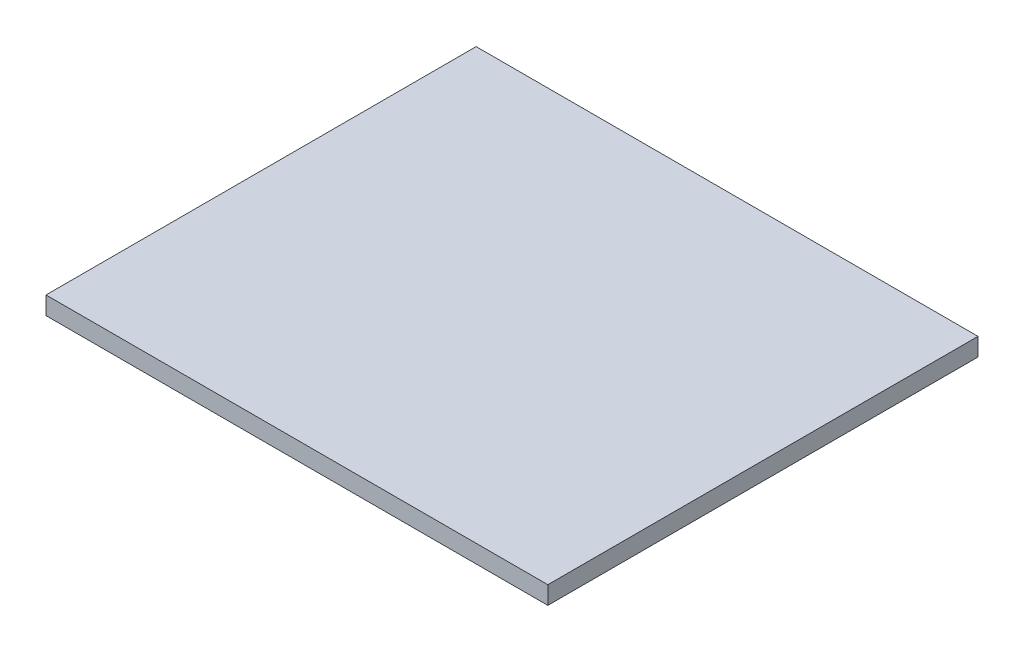
SolidWorks part; units mm, degrees
material "Oak"
ref_plane "Front Plane" through (0, 0, 0) normal (0, 0, 1) x (1, 0, 0)
ref_plane "Top Plane" through (0, 0, 0) normal (0, 1, 0) x (1, 0, 0)
ref_plane "Right Plane" through (0, 0, 0) normal (1, 0, 0) x (0, 0, -1)
sketch "Sketch1" plane through (0, 0, 0) normal (0, 1, 0) x (1, 0, 0)
  line L1 (-88.9, -76.2) -> (88.9, -76.2)
  line L2 (-88.9, -76.2) -> (-88.9, 76.2)
  line L3 (-88.9, 76.2) -> (88.9, 76.2)
  line L4 (88.9, -76.2) -> (88.9, 76.2)
  line L5 (-88.9, -76.2) -> (88.9, 76.2) construction
  line L6 (-88.9, 76.2) -> (88.9, -76.2) construction
  point P0 (0, 0)
  dimension "D1" = 177.8
  dimension "D2" = 152.4
extrude "Boss-Extrude1" add sketch "Sketch1" along normal blind 6.35
